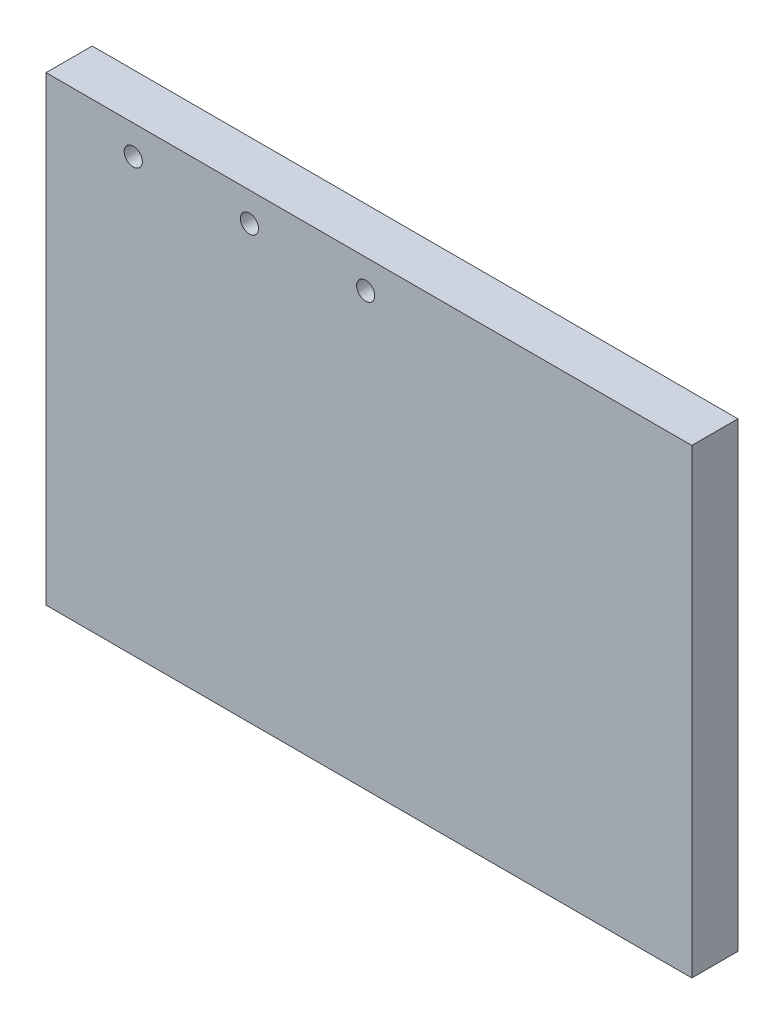
SolidWorks part; units mm, degrees
material "Balsa"
ref_plane "Front Plane" through (0, 0, 0) normal (0, 0, 1) x (1, 0, 0)
ref_plane "Top Plane" through (0, 0, 0) normal (0, 1, 0) x (1, 0, 0)
ref_plane "Right Plane" through (0, 0, 0) normal (1, 0, 0) x (0, 0, -1)
sketch "Sketch1" plane through (0, 0, 0) normal (0, 0, 1) x (1, 0, 0)
  line L1 (-44.45, 31.75) -> (44.45, 31.75)
  line L2 (-44.45, 31.75) -> (-44.45, -31.75)
  line L3 (-44.45, -31.75) -> (44.45, -31.75)
  line L4 (44.45, 31.75) -> (44.45, -31.75)
  line L5 (-44.45, 31.75) -> (44.45, -31.75) construction
  line L6 (-44.45, -31.75) -> (44.45, 31.75) construction
  point P0 (0, 0)
  dimension "D5" = 88.9
  dimension "D6" = 63.5
extrude "Boss-Extrude1" add sketch "Sketch1" along normal blind 6.35
sketch "Sketch2" plane through (0, 0, 0) normal (0, 0, -1) x (-1, 0, 0)
  line L0 (44.45, 31.75) -> (-44.45, 31.75) construction
  line L1 (44.45, 31.75) -> (32.45, 31.75) construction
  line L2 (44.45, 31.75) -> (44.45, 27.75) construction
  line L3 (44.45, 27.75) -> (32.45, 27.75) construction
  line L4 (32.45, 31.75) -> (32.45, 27.75) construction
  line L5 (44.45, 31.75) -> (44.45, -31.75) construction
  line L6 (32.45, 27.75) -> (0.45, 27.75) construction
  circle A0 centre (0.45, 27.75) radius 1.25
  circle A1 centre (32.45, 27.75) radius 1.25
  circle A2 centre (16.45, 27.75) radius 1.25
  dimension "D4" = 2.5
  dimension "D1" = 4
  dimension "D2" = 12
  dimension "D3" = 16
extrude "Cut-Extrude1" cut sketch "Sketch2" against normal through all
